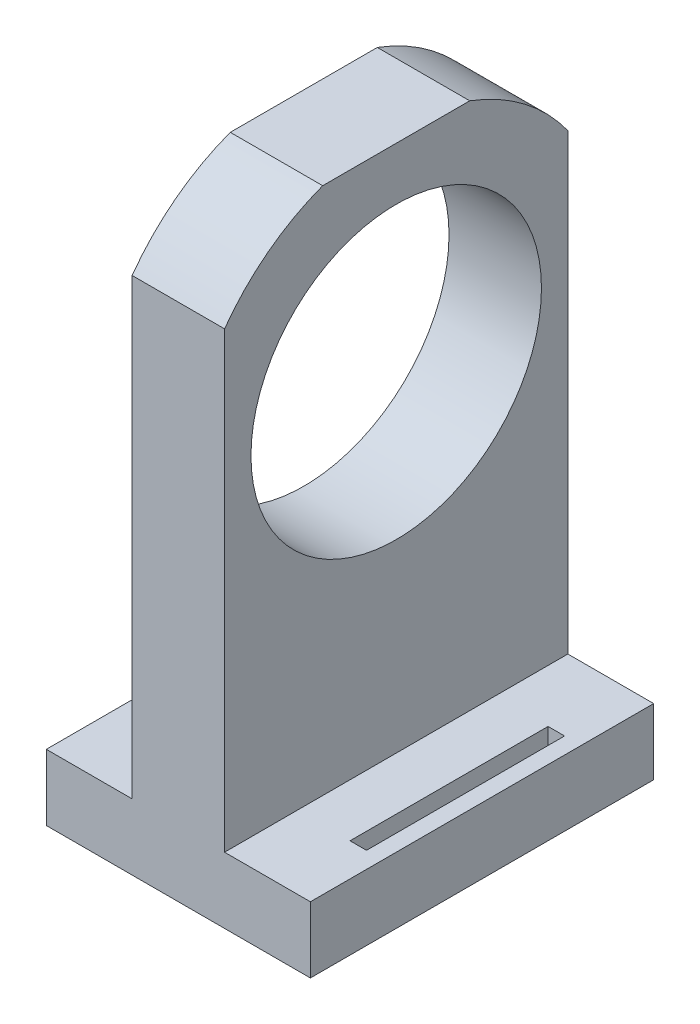
SolidWorks part; units mm, degrees
ref_plane "Front Plane" through (0, 0, 0) normal (0, 0, 1) x (1, 0, 0)
ref_plane "Top Plane" through (0, 0, 0) normal (0, 1, 0) x (1, 0, 0)
ref_plane "Right Plane" through (0, 0, 0) normal (1, 0, 0) x (0, 0, -1)
sketch "Sketch1" plane through (0, 0, 0) normal (0, 1, 0) x (1, 0, 0)
  line L0 (0, 0) -> (20, 0)
  line L1 (0, 0) -> (0, 26)
  line L2 (0, 26) -> (20, 26)
  line L3 (20, 26) -> (20, 0)
  line L4 (0, 26) -> (1.6662, 26)
  line L5 (2.5, 20.5) -> (2.5, 5.5)
  line L6 (20, 26) -> (16.6758, 26)
  line L7 (17.5008, 20.5) -> (17.5008, 5.5)
  line L8 (0, 26) -> (0.8331, 26)
  line L9 (1.25, 20.5) -> (1.25, 5.5)
  line L10 (18.7508, 20.5) -> (18.7508, 5.5)
  line L12 (17.5008, 20.5) -> (18.7508, 20.5)
  line L13 (0, 13) -> (20, 13) construction
  line L14 (17.5008, 5.5) -> (18.7508, 5.5)
  line L16 (2.5, 20.5) -> (1.25, 20.5)
  line L18 (2.5, 5.5) -> (1.25, 5.5)
  line L19 (10, 26) -> (10, 0) construction
  line L28 (14.1758, 26) -> (10, 26)
  dimension "D1" = 20
  dimension "D2" = 26
  dimension "D3" = 15
  dimension "D4" = 7.5
  dimension "D5" = 15.0008
  dimension "D6" = 7.5
  dimension "D7" = 1.25
sketch "Sketch2" plane through (0, 0, 0) normal (0, 1, 0) x (1, 0, 0)
  line L0 (2.5, 20.5) -> (4.675, 20.5)
  line L1 (4.675, 20.5) -> (7.4624, 20.5)
  line L2 (7.4624, 20.5) -> (10.4624, 20.5)
  line L3 (13.4624, 20.5) -> (10.4624, 20.5)
  line L4 (13.4624, 20.5) -> (16.2609, 20.5)
extrude "Boss-Extrude5" add sketch "Sketch1" along normal blind 5
sketch "Sketch3" plane through (0, 5, 0) normal (0, 1, 0) x (1, 0, 0)
  line L0 (2.5, 20.5) -> (2.5, 5.5) construction
  line L5 (6.5, 0) -> (13.5, 0)
  line L6 (6.5, 0) -> (6.5, 26)
  line L7 (6.5, 26) -> (13.5, 26)
  line L8 (13.5, 0) -> (13.5, 26)
  line L9 (6.5, 0) -> (13.5, 26) construction
  line L10 (6.5, 26) -> (13.5, 0) construction
  line L11 (0, 26) -> (20, 26) construction
  point P0 (10, 13)
  point P9 (0, 0)
  dimension "D1" = 7.5
  dimension "D2" = 7
  dimension "D3" = 26
  dimension "D4" = 13
extrude "Boss-Extrude6" add sketch "Sketch3" along normal blind 40
sketch "Sketch5" plane through (13.5, 0, 0) normal (1, 0, 0) x (0, 0, -1)
  line L0 (7.4322, 45) -> (0, 45)
  line L1 (26, 5) -> (0, 5) construction
  line L2 (13, 45) -> (13, 5) construction
  line L3 (0, 45) -> (26, 45) construction
  line L4 (0, 5) -> (26, 5) construction
  line L8 (0, 5) -> (26, 5)
  line L9 (26, 5) -> (26, 45)
  line L10 (26, 45) -> (0, 45)
  line L11 (0, 45) -> (0, 5)
  line L13 (26, 39.3274) -> (26, 45)
  line L14 (26, 45) -> (18.5678, 45)
  line L15 (0, 45) -> (0, 39.3274)
  circle A0 centre (13, 30) radius 11
  arc A1 (26, 39.3274) -> (18.5678, 45) centre (13, 30) ccw
  arc A2 (7.4322, 45) -> (0, 39.3274) centre (13, 30) ccw
  dimension "D1" = 32
  dimension "D2" = 22
  dimension "D3" = 25
  dimension "D4" = 0
extrude "Cut-Extrude1" cut sketch "Sketch5" against normal up to next
